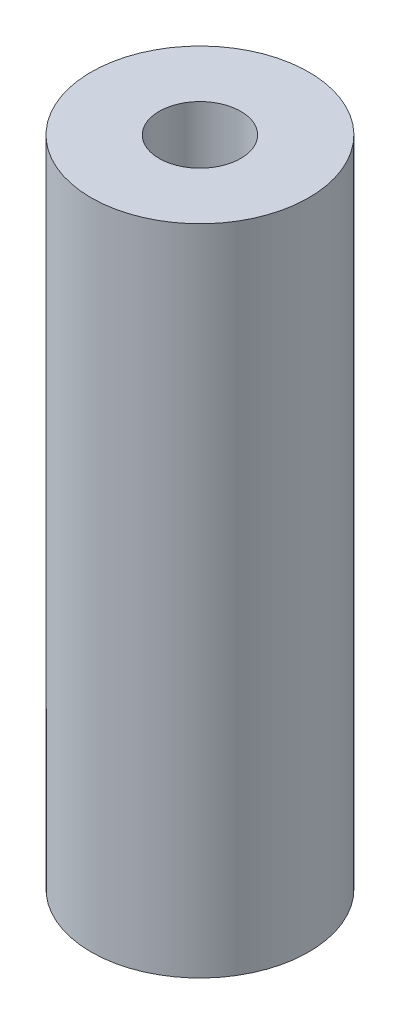
SolidWorks part; units mm, degrees
ref_plane "Front Plane" through (0, 0, 0) normal (0, 0, 1) x (1, 0, 0)
ref_plane "Top Plane" through (0, 0, 0) normal (0, 1, 0) x (1, 0, 0)
ref_plane "Right Plane" through (0, 0, 0) normal (1, 0, 0) x (0, 0, -1)
sketch "Sketch1" plane through (0, 0, 0) normal (0, 1, 0) x (1, 0, 0)
  circle A0 centre (0, 0) radius 4
  dimension "D1" = 8
extrude "Boss-Extrude1" add sketch "Sketch1" along normal blind 24
sketch "Sketch2" plane through (0, 24, 0) normal (0, 1, 0) x (1, 0, 0)
  circle A0 centre (0, 0) radius 1.5
  dimension "D1" = 3
extrude "Cut-Extrude1" cut sketch "Sketch2" against normal through all
